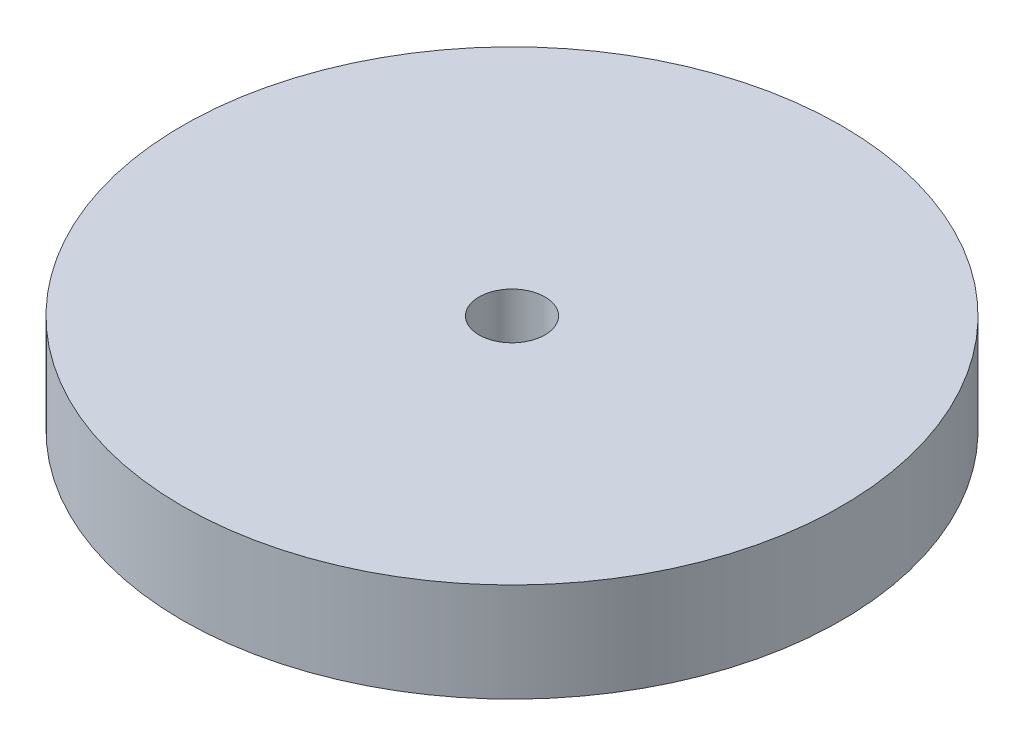
SolidWorks part; units mm, degrees
ref_plane "Front Plane" through (0, 0, 0) normal (0, 0, 1) x (1, 0, 0)
ref_plane "Top Plane" through (0, 0, 0) normal (0, 1, 0) x (1, 0, 0)
ref_plane "Right Plane" through (0, 0, 0) normal (1, 0, 0) x (0, 0, -1)
sketch "Sketch1" plane through (0, 0, 0) normal (0, 1, 0) x (1, 0, 0)
  circle A0 centre (0, 0) radius 10
  dimension "D1" = 20
extrude "Boss-Extrude1" add sketch "Sketch1" along normal blind 3
sketch "Sketch2" plane through (0, 3, 0) normal (0, 1, 0) x (1, 0, 0)
  circle A0 centre (0, 0) radius 1
  dimension "D1" = 2
extrude "Cut-Extrude1" cut sketch "Sketch2" against normal blind 10
